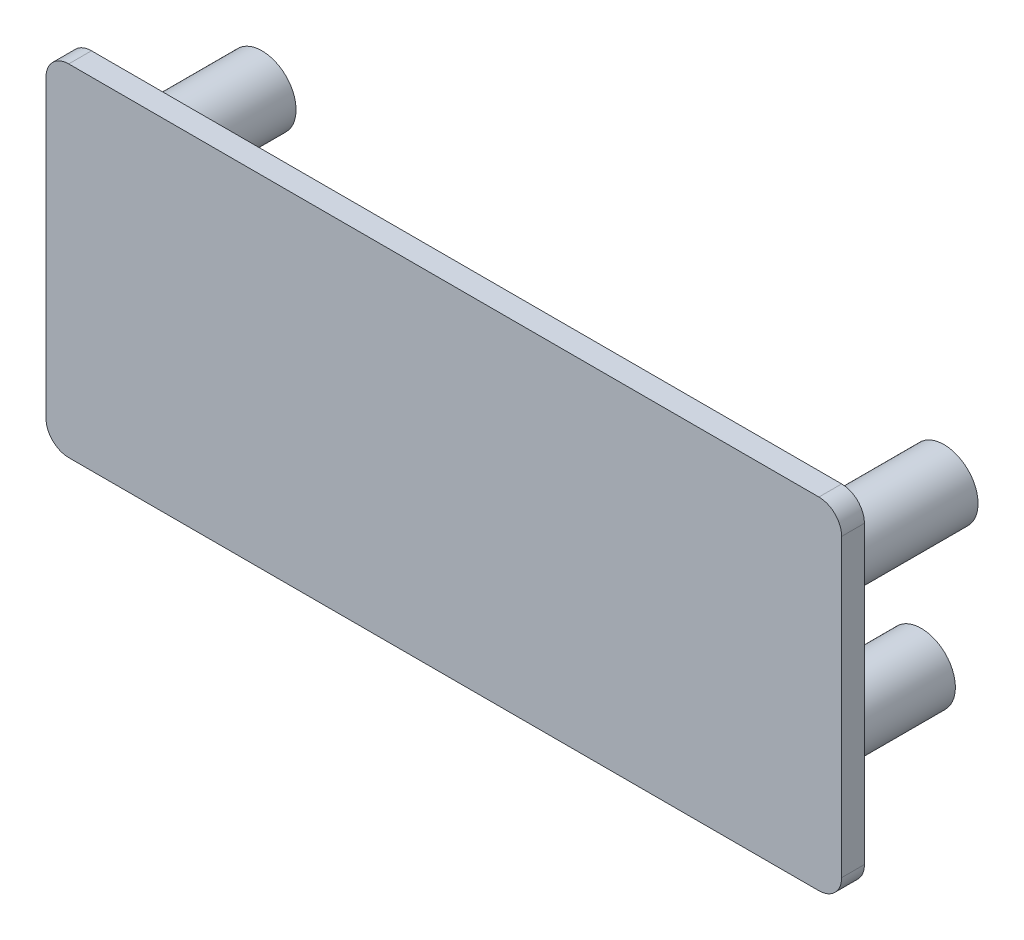
SolidWorks part; units mm, degrees
ref_plane "Front Plane" through (0, 0, 0) normal (0, 0, 1) x (1, 0, 0)
ref_plane "Top Plane" through (0, 0, 0) normal (0, 1, 0) x (1, 0, 0)
ref_plane "Right Plane" through (0, 0, 0) normal (1, 0, 0) x (0, 0, -1)
sketch "Sketch1" plane through (0, 0, 0) normal (0, 0, 1) x (1, 0, 0)
  line L1 (-33, -15) -> (33, -15)
  line L2 (-35, -13) -> (-35, 13)
  line L3 (-33, 15) -> (33, 15)
  line L4 (35, -13) -> (35, 13)
  line L5 (-35, -15) -> (35, 15) construction
  line L6 (-35, 15) -> (35, -15) construction
  arc A0 (-33, -15) -> (-35, -13) centre (-33, -13) cw
  arc A1 (33, -15) -> (35, -13) centre (33, -13) ccw
  arc A2 (33, 15) -> (35, 13) centre (33, 13) cw
  arc A3 (-35, 13) -> (-33, 15) centre (-33, 13) cw
  point P0 (0, 0)
  dimension "D3" = 2
  dimension "D1" = 30
  dimension "D2" = 70
extrude "Boss-Extrude1" add sketch "Sketch1" along normal blind 2
sketch "Sketch2" plane through (0, 0, 0) normal (0, 0, -1) x (-1, 0, 0)
  line L0 (0, 0) -> (-50000, 0) construction
  line L1 (0, 0) -> (0, -50000) construction
  line L2 (28, 0) -> (28, -15) construction
  line L3 (33, -15) -> (-33, -15) construction
  line L4 (-28, 0) -> (-28, -15) construction
  line L5 (-30, 15) -> (-30, 0) construction
  line L6 (-33, 15) -> (33, 15) construction
  circle A0 centre (28, -7.5) radius 1.95
  circle A1 centre (-28, -7.5) radius 1.95
  circle A2 centre (-30, 7.5) radius 1.95
  circle A3 centre (30, 7.5) radius 1.95
  circle A4 centre (28, -7.5) radius 3
  circle A5 centre (30, 7.5) radius 3
  circle A6 centre (-30, 7.5) radius 3
  circle A7 centre (-28, -7.5) radius 3
  point P17 (28, -7.5)
  point P20 (-28, -7.5)
  point P25 (-30, 7.5)
  point P26 (0, 0)
  dimension "D3" = 3.9
  dimension "D1" = 28
  dimension "D2" = 28
  dimension "D4" = 30
  dimension "D5" = 30
  dimension "D6" = 1.05
extrude "Boss-Extrude2" add sketch "Sketch2" along normal blind 12
